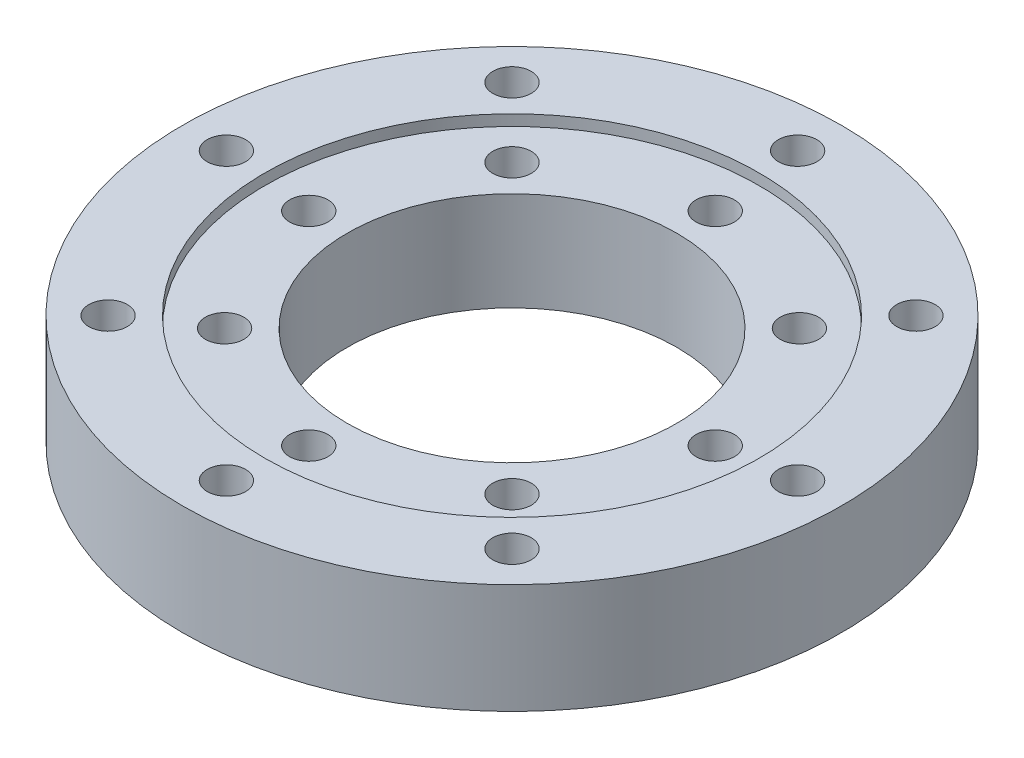
SolidWorks part; units mm, degrees
ref_plane "Front Plane" through (0, 0, 0) normal (0, 0, 1) x (1, 0, 0)
ref_plane "Top Plane" through (0, 0, 0) normal (0, 1, 0) x (1, 0, 0)
ref_plane "Right Plane" through (0, 0, 0) normal (1, 0, 0) x (0, 0, -1)
sketch "Sketch1" plane through (0, 0, 0) normal (0, 1, 0) x (1, 0, 0)
  circle A0 centre (0, 0) radius 30
  dimension "D1" = 60
extrude "Boss-Extrude1" add sketch "Sketch1" along normal blind 10
sketch "Sketch2" plane through (0, 10, 0) normal (0, 1, 0) x (1, 0, 0)
  circle A0 centre (0, 0) radius 15
  dimension "D1" = 30
extrude "Cut-Extrude1" cut sketch "Sketch2" against normal through all
sketch "Sketch3" plane through (0, 10, 0) normal (0, 1, 0) x (1, 0, 0)
  circle A0 centre (0, 0) radius 22.5
  dimension "D1" = 45
extrude "Cut-Extrude2" cut sketch "Sketch3" against normal blind 1
sketch "Sketch4" plane through (0, 9, 0) normal (0, 1, 0) x (1, 0, 0)
  circle A0 centre (0, 18.5) radius 1.75
  point P2 (0, 0)
  point P5 (0, 18.4411)
  dimension "D1" = 3.5
  dimension "D2" = 18.5
extrude "Cut-Extrude3" cut sketch "Sketch4" against normal through all
pattern_circular "CirPattern1" count 8 over 360 about axis through (0, 0, 0) along (0, 1, 0) of "Cut-Extrude3"
sketch "Sketch5" plane through (0, 10, 0) normal (0, 1, 0) x (1, 0, 0)
  circle A0 centre (0, 26) radius 1.75
  point P2 (0, 0)
  dimension "D1" = 3.5
  dimension "D2" = 26
extrude "Cut-Extrude4" cut sketch "Sketch5" against normal through all
pattern_circular "CirPattern2" count 8 over 360 about axis through (0, 0, 0) along (0, 1, 0) of "Cut-Extrude4"
